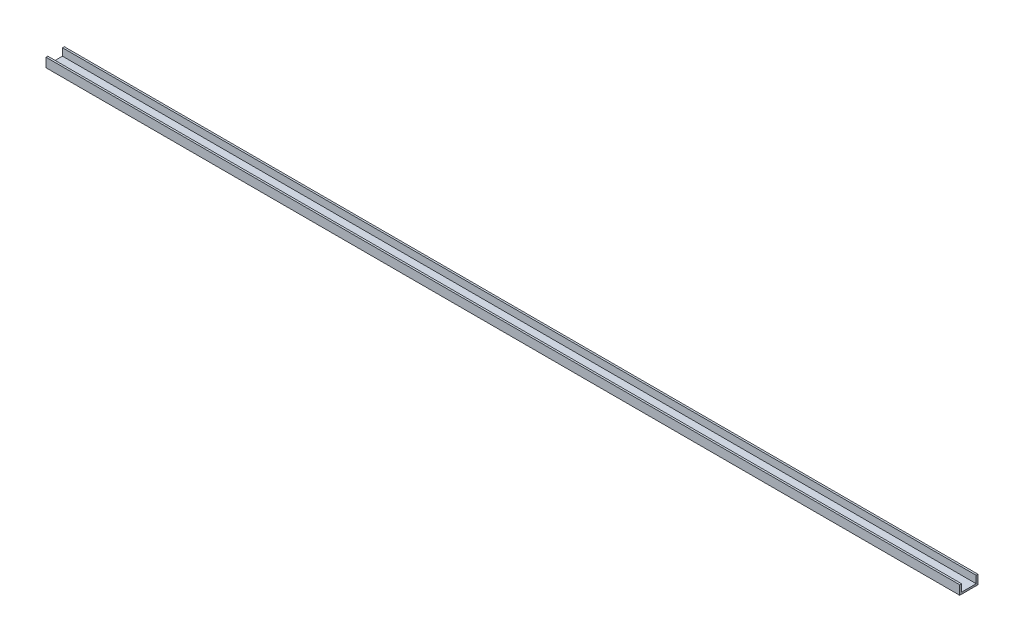
SolidWorks part; units mm, degrees
ref_plane "Front Plane" through (0, 0, 0) normal (0, 0, 1) x (1, 0, 0)
ref_plane "Top Plane" through (0, 0, 0) normal (0, 1, 0) x (1, 0, 0)
ref_plane "Right Plane" through (0, 0, 0) normal (1, 0, 0) x (0, 0, -1)
sketch "Sketch2" plane through (0, 0, 0) normal (1, 0, 0) x (0, 0, -1)
  line L0 (0, 10) -> (0, 0)
  line L1 (0, 0) -> (20, 0)
  line L2 (20, 0) -> (20, 10)
  line L3 (20, 10) -> (18, 10)
  line L4 (18, 10) -> (18, 2)
  line L5 (18, 2) -> (2, 2)
  line L6 (2, 2) -> (2, 10)
  line L7 (2, 10) -> (0, 10)
  dimension "D1" = 20
  dimension "D2" = 16
  dimension "D3" = 2
  dimension "D4" = 2
  dimension "D5" = 10
  dimension "D6" = 10
  dimension "D7" = 2
extrude "Boss-Extrude1" add sketch "Sketch2" along normal blind 1000
